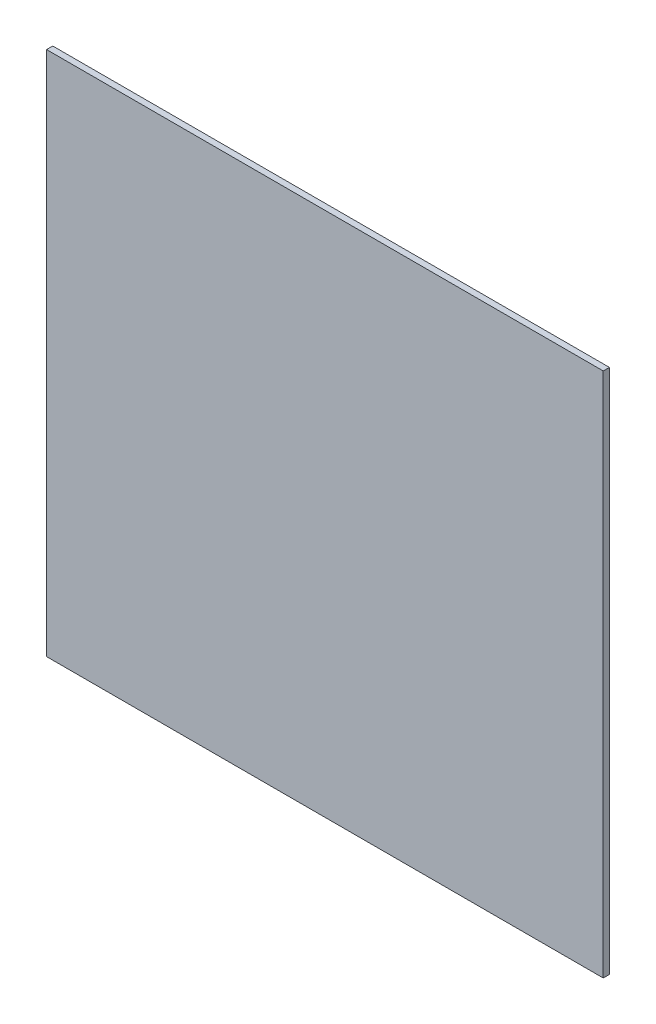
SolidWorks part; units mm, degrees
ref_plane "Front Plane" through (0, 0, 0) normal (0, 0, 1) x (1, 0, 0)
ref_plane "Top Plane" through (0, 0, 0) normal (0, 1, 0) x (1, 0, 0)
ref_plane "Right Plane" through (0, 0, 0) normal (1, 0, 0) x (0, 0, -1)
sketch "Sketch1" plane through (0, 0, 0) normal (0, 0, 1) x (1, 0, 0)
  line L0 (0, 170) -> (0, 0) construction
  line L1 (-180, 170) -> (180, 170)
  line L2 (-180, 170) -> (-180, -170)
  line L3 (-180, -170) -> (180, -170)
  line L4 (180, 170) -> (180, -170)
  line L5 (0, 0) -> (0, -170) construction
  dimension "D1" = 340
  dimension "D2" = 360
extrude "Boss-Extrude1" add sketch "Sketch1" along normal mid plane 4
